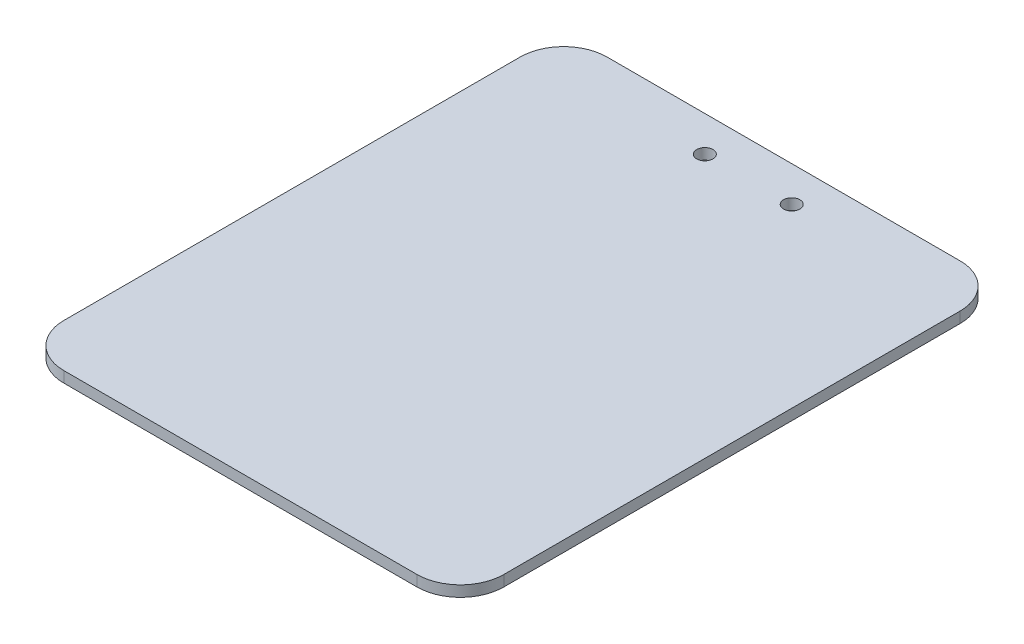
SolidWorks part; units mm, degrees
ref_plane "Front Plane" through (0, 0, 0) normal (0, 0, 1) x (1, 0, 0)
ref_plane "Top Plane" through (0, 0, 0) normal (0, 1, 0) x (1, 0, 0)
ref_plane "Right Plane" through (0, 0, 0) normal (1, 0, 0) x (0, 0, -1)
sketch "Sketch1" plane through (0, 0, 0) normal (0, 1, 0) x (1, 0, 0)
  line L0 (0, 50) -> (81, 50) construction
  line L1 (8, 0) -> (73, 0)
  line L2 (0, 8) -> (0, 92)
  line L3 (8, 100) -> (73, 100)
  line L4 (81, 8) -> (81, 92)
  line L5 (40.5, 100) -> (40.5, 0) construction
  circle A0 centre (48.5, 93.5) radius 1.5
  circle A1 centre (32.5, 93.5) radius 1.5
  arc A2 (8, 0) -> (0, 8) centre (8, 8) cw
  arc A3 (73, 0) -> (81, 8) centre (73, 8) ccw
  arc A4 (73, 100) -> (81, 92) centre (73, 92) cw
  arc A5 (0, 92) -> (8, 100) centre (8, 92) cw
  point P15 (0, 0)
  point P18 (81, 0)
  point P23 (0, 100)
  dimension "D3" = 3
  dimension "D6" = 8
  dimension "D1" = 81
  dimension "D2" = 100
  dimension "D4" = 6.5
  dimension "D5" = 8
extrude "Boss-Extrude1" add sketch "Sketch1" along normal blind 2
